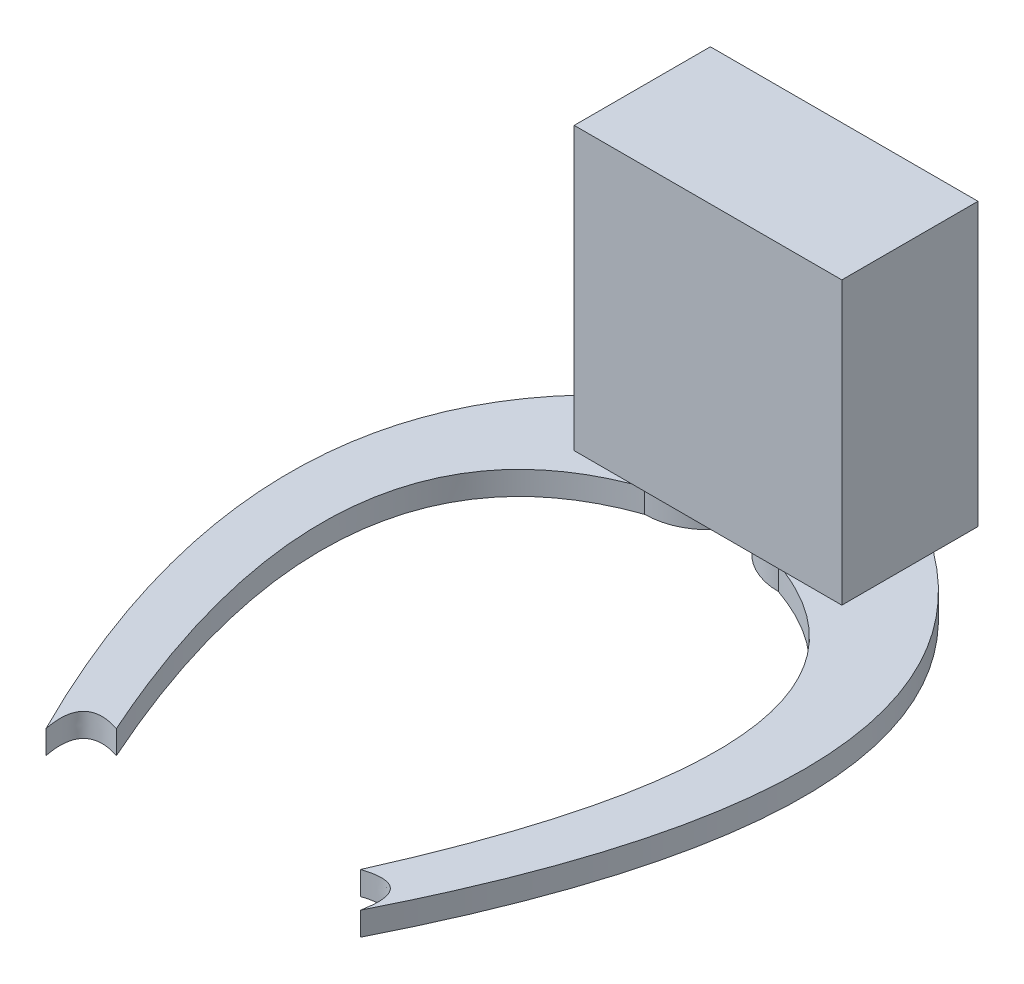
SolidWorks part; units mm, degrees
ref_plane "Alzado" through (0, 0, 0) normal (0, 0, 1) x (1, 0, 0)
ref_plane "Planta" through (0, 0, 0) normal (0, 1, 0) x (1, 0, 0)
ref_plane "Vista lateral" through (0, 0, 0) normal (1, 0, 0) x (0, 0, -1)
sketch "Croquis1" plane through (0, 0, 0) normal (0, 0, 1) x (1, 0, 0)
  line L1 (-11.4, 24) -> (11.4, 24)
  line L2 (-11.4, 24) -> (-11.4, 0)
  line L3 (-11.4, 0) -> (11.4, 0)
  line L4 (11.4, 24) -> (11.4, 0)
  dimension "D1" = 22.8
  dimension "D2" = 24
extrude "Saliente-Extruir2" add sketch "Croquis1" along normal blind 11.6
sketch "Croquis2" plane through (0, 0, 0) normal (0, -1, 0) x (1, 0, 0)
  line L0 (0, 11.6) -> (0, 0) construction
  line L1 (-11.4, 11.6) -> (11.4, 11.6) construction
  line L2 (-11.4, 11.6) -> (-11.4, 0) construction
  line L3 (-11.4, 0) -> (11.4, 0) construction
  line L4 (-11.4, 5.8) -> (11.4, 5.8) construction
  line L5 (11.4, 11.6) -> (11.4, 0) construction
  circle A0 centre (-5.7, 5.8) radius 2.5
  arc A1 (-5.7, 11.3) -> (-5.7, 0.3) centre (-5.7, 5.8) cw
  arc A2 (5.7, 11.3) -> (5.7, 0.3) centre (5.7, 5.8) ccw
  circle A3 centre (5.7, 5.8) radius 2.5
  spline S0 degree 2 poles (-5.7, 11.3) (-25.2903, 18.1952) (-10.4, 51.6) knots 0 0 0 1 1 1
  spline S1 degree 2 poles (-10.4, 51.6) (-14.2316, 50.3596) (-13.4, 54.6) knots 0 0 0 1 1 1
  spline S2 degree 2 poles (-13.4, 54.6) (-33.6503, 14.235) (-5.7, 0.3) knots 0 0 0 1 1 1
  spline S3 degree 2 poles (13.4, 54.6) (33.6503, 14.235) (5.7, 0.3) knots 0 0 0 1 1 1
  spline S4 degree 2 poles (10.4, 51.6) (14.2316, 50.3596) (13.4, 54.6) knots 0 0 0 1 1 1
  spline S5 degree 2 poles (5.7, 11.3) (25.2903, 18.1952) (10.4, 51.6) knots 0 0 0 1 1 1
  dimension "D2" = 5
  dimension "D3" = 3
  dimension "D4" = 3
  dimension "D8" = 46.2876
  dimension "D9" = 43
  dimension "D5" = 62.3662
  dimension "D1" = 5.7
  dimension "D6" = 1
  dimension "D7" = 0
  dimension "D10" = 2
  dimension "D11" = 5
extrude "Saliente-Extruir3" add sketch "Croquis2" along normal blind 2
